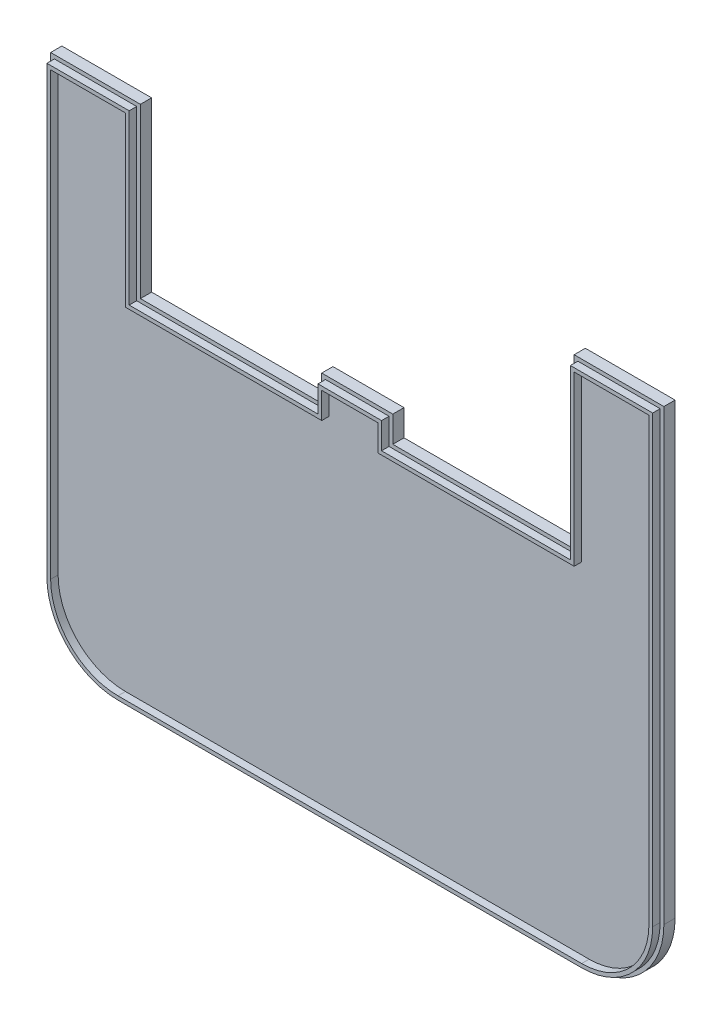
SolidWorks part; units mm, degrees
ref_plane "Plano frontal" through (0, 0, 0) normal (0, 0, 1) x (1, 0, 0)
ref_plane "Plano superior" through (0, 0, 0) normal (0, 1, 0) x (1, 0, 0)
ref_plane "Plano direito" through (0, 0, 0) normal (1, 0, 0) x (0, 0, -1)
sketch "Esboço1" plane through (0, 0, 0) normal (0, 0, 1) x (1, 0, 0)
  line L0 (-58, 35.5) -> (-58, 80.5)
  line L1 (-58, 80.5) -> (-82, 80.5)
  line L2 (-82, 80.5) -> (-82, -39.5)
  line L3 (-62, -59.5) -> (62, -59.5)
  line L4 (82, -39.5) -> (82, 80.5)
  line L5 (58, 80.5) -> (82, 80.5)
  line L6 (58, 35.5) -> (58, 80.5)
  line L7 (-9.5, 42.5) -> (9.5, 42.5)
  line L8 (-9.5, 35.5) -> (-9.5, 42.5)
  line L9 (-9.5, 35.5) -> (-58, 35.5)
  line L10 (9.5, 42.5) -> (9.5, 35.5)
  line L11 (9.5, 35.5) -> (58, 35.5)
  arc A0 (-82, -39.5) -> (-62, -59.5) centre (-62, -39.5) ccw
  arc A1 (62, -59.5) -> (82, -39.5) centre (62, -39.5) ccw
  dimension "D1" = 20
  dimension "D2" = 120
  dimension "D3" = 120
extrude "Ressalto-extrusão1" add sketch "Esboço1" along normal blind 3
sketch "Esboço2" plane through (0, 0, 3) normal (0, 0, 1) x (1, 0, 0)
  line L12 (-80, 78.5) -> (-80, -39.5)
  line L13 (-62, -57.5) -> (62, -57.5)
  line L14 (80, -39.5) -> (80, 78.5)
  line L15 (80, 78.5) -> (60, 78.5)
  line L16 (60, 78.5) -> (60, 33.5)
  line L17 (60, 33.5) -> (7.5, 33.5)
  line L18 (7.5, 33.5) -> (7.5, 40.5)
  line L19 (7.5, 40.5) -> (-7.5, 40.5)
  line L20 (-7.5, 40.5) -> (-7.5, 33.5)
  line L21 (-7.5, 33.5) -> (-60, 33.5)
  line L22 (-60, 33.5) -> (-60, 78.5)
  line L23 (-60, 78.5) -> (-80, 78.5)
  line L24 (-8.5, 34.5) -> (-59, 34.5)
  line L25 (-59, 34.5) -> (-59, 79.5)
  line L26 (-59, 79.5) -> (-81, 79.5)
  line L27 (-81, 79.5) -> (-81, -39.5)
  line L28 (-62, -58.5) -> (62, -58.5)
  line L29 (81, -39.5) -> (81, 79.5)
  line L30 (81, 79.5) -> (59, 79.5)
  line L31 (59, 79.5) -> (59, 34.5)
  line L32 (59, 34.5) -> (8.5, 34.5)
  line L33 (8.5, 34.5) -> (8.5, 41.5)
  line L34 (8.5, 41.5) -> (-8.5, 41.5)
  line L35 (-8.5, 41.5) -> (-8.5, 34.5)
  line L36 (-8.5, 34.5) -> (-59, 34.5)
  line L37 (-59, 34.5) -> (-59, 79.5)
  line L38 (-59, 79.5) -> (-81, 79.5)
  line L39 (-81, 79.5) -> (-81, -39.5)
  line L40 (-62, -58.5) -> (62, -58.5)
  line L41 (81, -39.5) -> (81, 79.5)
  line L42 (81, 79.5) -> (59, 79.5)
  line L43 (59, 79.5) -> (59, 34.5)
  line L44 (59, 34.5) -> (8.5, 34.5)
  line L45 (8.5, 34.5) -> (8.5, 41.5)
  line L46 (8.5, 41.5) -> (-8.5, 41.5)
  line L47 (-8.5, 41.5) -> (-8.5, 34.5)
  arc A2 (-80, -39.5) -> (-62, -57.5) centre (-62, -39.5) ccw
  arc A3 (62, -57.5) -> (80, -39.5) centre (62, -39.5) ccw
  arc A4 (-81, -39.5) -> (-62, -58.5) centre (-62, -39.5) ccw
  arc A5 (62, -58.5) -> (81, -39.5) centre (62, -39.5) ccw
  arc A6 (-81, -39.5) -> (-62, -58.5) centre (-62, -39.5) ccw
  arc A7 (62, -58.5) -> (81, -39.5) centre (62, -39.5) ccw
  dimension "D1" = 1
  dimension "D2" = 1
extrude "Ressalto-extrusão2" add sketch "Esboço2" along normal blind 2
